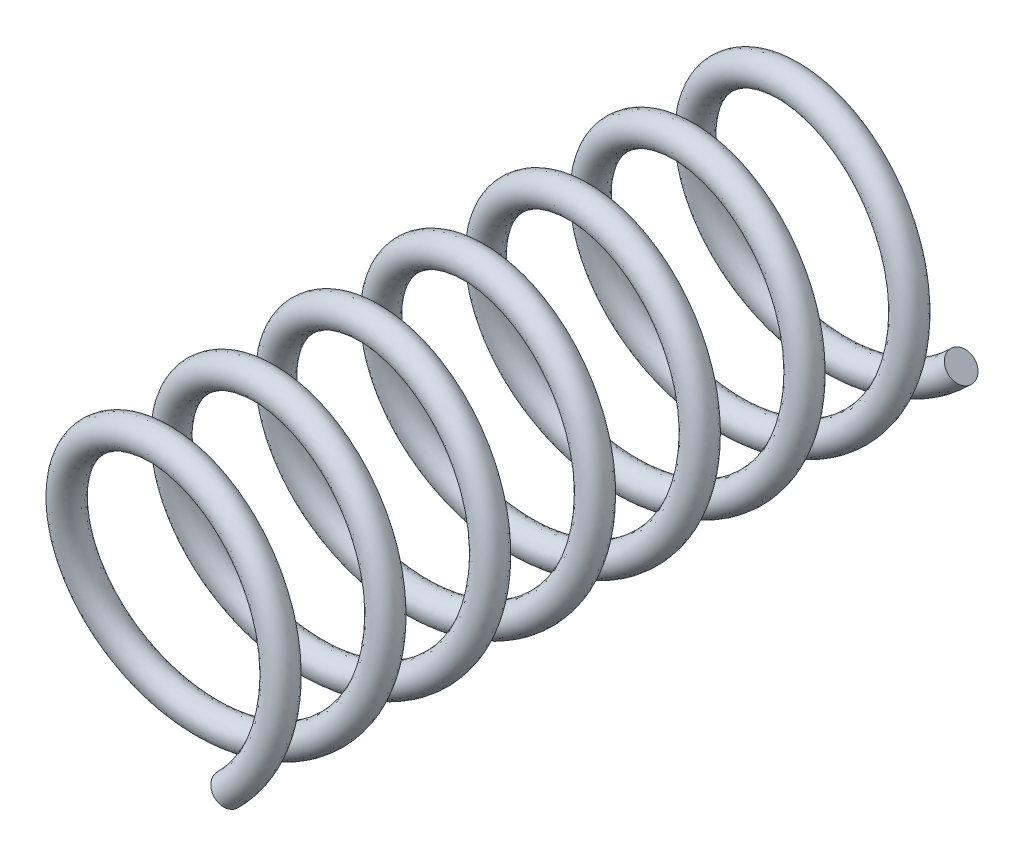
SolidWorks part; units mm, degrees
ref_plane "Alzado" through (0, 0, 0) normal (0, 0, 1) x (1, 0, 0)
ref_plane "Planta" through (0, 0, 0) normal (0, 1, 0) x (1, 0, 0)
ref_plane "Vista lateral" through (0, 0, 0) normal (1, 0, 0) x (0, 0, -1)
sketch "Croquis1" plane through (0, 0, 0) normal (0, 0, 1) x (1, 0, 0)
  circle A0 centre (0, 0) radius 9
  dimension "D1" = 18
curve "Hélice/Espiral1" pitch 7.1429 height 50 turns 7
sweep "Barrer1" add path "Hélice/Espiral1" circular profile diameter 2 parameters "D3"=2
ref_plane "Plano1" through (0, 0, 50) normal (0, 0, 1) x (1, 0, 0)
sketch "Croquis90" plane through (0, 0, 0) normal (0, 1, 0) x (1, 0, 0)
  line L0 (0, 0) -> (0, -58.6757) construction
